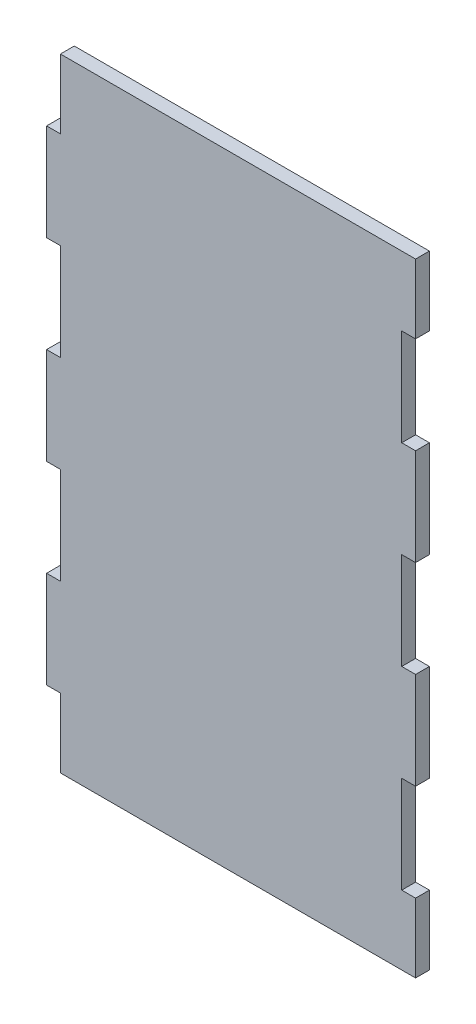
SolidWorks part; units mm, degrees
ref_plane "Plano frontal" through (0, 0, 0) normal (0, 0, 1) x (1, 0, 0)
ref_plane "Plano superior" through (0, 0, 0) normal (0, 1, 0) x (1, 0, 0)
ref_plane "Plano direito" through (0, 0, 0) normal (1, 0, 0) x (0, 0, -1)
sketch "Esboço1" plane through (0, 0, 0) normal (0, 0, 1) x (1, 0, 0)
  line L1 (38.5, -67.5) -> (-38.5, -67.5)
  line L2 (38.5, -67.5) -> (38.5, 67.5)
  line L3 (38.5, 67.5) -> (-38.5, 67.5)
  line L4 (-38.5, -67.5) -> (-38.5, 67.5)
  line L5 (38.5, -67.5) -> (-38.5, 67.5) construction
  line L6 (38.5, 67.5) -> (-38.5, -67.5) construction
  point P0 (0, 0)
  dimension "D1" = 77
  dimension "D2" = 135
extrude "Ressalto-extrusão1" add sketch "Esboço1" along normal blind 3
sketch "Esboço4" plane through (0, 0, 3) normal (0, 0, 1) x (1, 0, 0)
  line L0 (38.5, -67.5) -> (38.5, 67.5) construction
  line L1 (38.5, 52.5) -> (35.5, 52.5)
  line L2 (38.5, 52.5) -> (38.5, 31.5)
  line L3 (38.5, 31.5) -> (35.5, 31.5)
  line L4 (35.5, 52.5) -> (35.5, 31.5)
  line L5 (38.5, 67.5) -> (-38.5, 67.5) construction
  line L6 (35.5, 10.5) -> (35.5, -10.5)
  line L7 (38.5, 10.5) -> (38.5, -10.5)
  line L8 (38.5, 10.5) -> (35.5, 10.5)
  line L9 (38.5, -10.5) -> (35.5, -10.5)
  line L10 (35.5, -31.5) -> (35.5, -52.5)
  line L11 (38.5, -31.5) -> (38.5, -52.5)
  line L12 (38.5, -31.5) -> (35.5, -31.5)
  line L13 (38.5, -52.5) -> (35.5, -52.5)
  dimension "D1" = 3
  dimension "D2" = 21
  dimension "D3" = 15
  dimension "D5" = 21
  dimension "D4" = 3
extrude "Corte-extrusão1" cut sketch "Esboço4" against normal through all
sketch "Esboço5" plane through (0, 0, 3) normal (0, 0, 1) x (1, 0, 0)
  line L0 (-38.5, 67.5) -> (-38.5, -67.5) construction
  line L1 (-38.5, 52.5) -> (-41.5, 52.5)
  line L2 (-38.5, 52.5) -> (-38.5, 31.5)
  line L3 (-38.5, 31.5) -> (-41.5, 31.5)
  line L4 (-41.5, 52.5) -> (-41.5, 31.5)
  line L7 (35.5, 31.5) -> (38.5, 31.5) construction
  line L8 (38.5, 52.5) -> (35.5, 52.5) construction
  dimension "D1" = 3
extrude "Ressalto-extrusão2" add sketch "Esboço5" against normal blind 3
pattern_linear "Padrão linear1" count 3 spacing 42 along (0, -1, 0) of "Ressalto-extrusão2"
